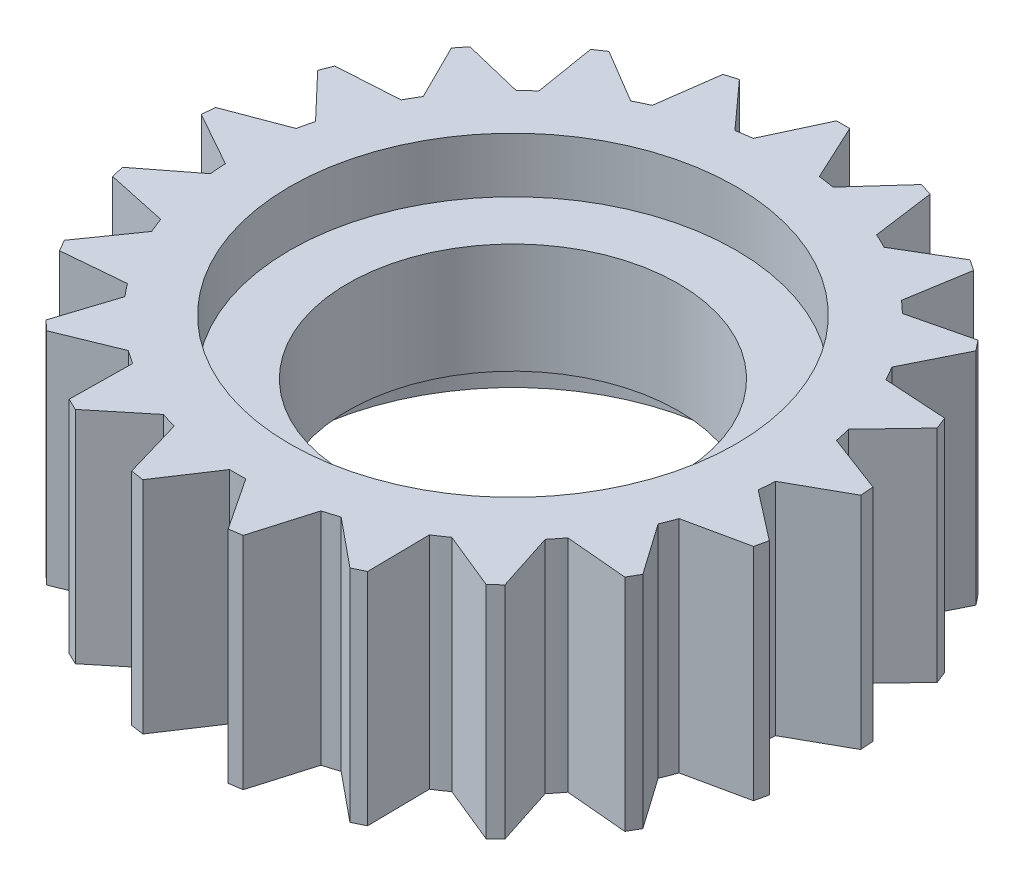
SolidWorks part; units mm, degrees
ref_plane "Front Plane" through (0, 0, 0) normal (0, 0, 1) x (1, 0, 0)
ref_plane "Top Plane" through (0, 0, 0) normal (0, 1, 0) x (1, 0, 0)
ref_plane "Right Plane" through (0, 0, 0) normal (1, 0, 0) x (0, 0, -1)
sketch "Sketch1" plane through (0, 0, 0) normal (1, 0, 0) x (0, 0, -1)
  line L0 (0, 0) -> (0, 16285.2798) construction
  line L1 (0, 0) -> (16285.2798, 0) construction
  line L2 (20.25, 10) -> (30, 10)
  line L3 (30, 10) -> (30, -10)
  line L4 (30, -10) -> (20.25, -10)
  line L5 (20.25, -10) -> (20.25, -5)
  line L6 (20.25, -5) -> (15, -5)
  line L7 (15, -5) -> (15, 5)
  line L8 (15, 5) -> (20.25, 5)
  line L9 (20.25, 5) -> (20.25, 10)
  dimension "D1" = 60
  dimension "D2" = 40.5
  dimension "D3" = 30
  dimension "D4" = 10
  dimension "D5" = 20
revolve "Revolve1" add sketch "Sketch1" angle 360 about L0
sketch "Sketch2" plane through (0, 10, 0) normal (0, 1, 0) x (1, 0, 0)
  line L0 (0, 0) -> (50000, 0) construction
  line L1 (0, 0) -> (0, 50000) construction
  line L2 (-0.6, 29.9781) -> (0.6, 29.9781)
  line L3 (0.6, 29.9781) -> (3, 24.8193)
  line L4 (-0.6, 29.9781) -> (-3, 24.8193)
  line L5 (8.2629, 28.8231) -> (4.4489, 24.601)
  line L6 (8.2629, 28.8231) -> (9.4095, 28.4694)
  line L7 (9.4095, 28.4694) -> (10.1823, 22.8324)
  line L8 (16.3915, 25.107) -> (11.5025, 22.1967)
  line L9 (16.3915, 25.107) -> (17.383, 24.4311)
  line L10 (17.383, 24.4311) -> (16.46, 18.8167)
  line L11 (23.0637, 19.1601) -> (17.5341, 17.8201)
  line L12 (23.0637, 19.1601) -> (23.8119, 18.2219)
  line L13 (23.8119, 18.2219) -> (21.275, 13.1291)
  line L14 (27.6866, 11.5107) -> (22.0077, 11.8601)
  line L15 (27.6866, 11.5107) -> (28.125, 10.3937)
  line L16 (28.125, 10.3937) -> (24.1997, 6.2749)
  line L17 (29.8494, 2.8386) -> (24.5258, 4.8464)
  line L18 (29.8494, 2.8386) -> (29.9391, 1.6419)
  line L19 (29.9391, 1.6419) -> (24.9741, -1.1369)
  line L20 (29.36, -6.0858) -> (24.8646, -2.598)
  line L21 (29.36, -6.0858) -> (29.093, -7.2557)
  line L22 (29.093, -7.2557) -> (23.5295, -8.4476)
  line L23 (26.2618, -14.4694) -> (22.9942, -9.8116)
  line L24 (26.2618, -14.4694) -> (25.6618, -15.5087)
  line L25 (25.6618, -15.5087) -> (19.9942, -15.0077)
  line L26 (20.8301, -21.5674) -> (19.0806, -16.1534)
  line L27 (20.8301, -21.5674) -> (19.9504, -22.3836)
  line L28 (19.9504, -22.3836) -> (14.6823, -20.2344)
  line L29 (13.5476, -26.749) -> (13.4716, -21.0598)
  line L30 (13.5476, -26.749) -> (12.4664, -27.2696)
  line L31 (12.4664, -27.2696) -> (8.0658, -23.6631)
  line L32 (5.0613, -29.5538) -> (6.6656, -24.095)
  line L33 (5.0613, -29.5538) -> (3.8747, -29.7327)
  line L34 (3.8747, -29.7327) -> (0.7326, -24.9893)
  line L35 (-3.8747, -29.7327) -> (-0.7326, -24.9893)
  line L36 (-3.8747, -29.7327) -> (-5.0613, -29.5538)
  line L37 (-5.0613, -29.5538) -> (-6.6656, -24.095)
  line L38 (-12.4664, -27.2696) -> (-8.0658, -23.6631)
  line L39 (-12.4664, -27.2696) -> (-13.5476, -26.749)
  line L40 (-13.5476, -26.749) -> (-13.4716, -21.0598)
  line L41 (-19.9504, -22.3836) -> (-14.6823, -20.2344)
  line L42 (-19.9504, -22.3836) -> (-20.8301, -21.5674)
  line L43 (-20.8301, -21.5674) -> (-19.0806, -16.1534)
  line L44 (-25.6618, -15.5087) -> (-19.9942, -15.0077)
  line L45 (-25.6618, -15.5087) -> (-26.2618, -14.4694)
  line L46 (-26.2618, -14.4694) -> (-22.9942, -9.8116)
  line L47 (-29.093, -7.2557) -> (-23.5295, -8.4476)
  line L48 (-29.093, -7.2557) -> (-29.36, -6.0858)
  line L49 (-29.36, -6.0858) -> (-24.8646, -2.598)
  line L50 (-29.9391, 1.6419) -> (-24.9741, -1.1369)
  line L51 (-29.9391, 1.6419) -> (-29.8494, 2.8386)
  line L52 (-29.8494, 2.8386) -> (-24.5258, 4.8464)
  line L53 (-28.125, 10.3937) -> (-24.1997, 6.2749)
  line L54 (-28.125, 10.3937) -> (-27.6866, 11.5107)
  line L55 (-27.6866, 11.5107) -> (-22.0077, 11.8601)
  line L56 (-23.8119, 18.2219) -> (-21.275, 13.1291)
  line L57 (-23.8119, 18.2219) -> (-23.0637, 19.1601)
  line L58 (-23.0637, 19.1601) -> (-17.5341, 17.8201)
  line L59 (-17.383, 24.4311) -> (-16.46, 18.8167)
  line L60 (-17.383, 24.4311) -> (-16.3915, 25.107)
  line L61 (-16.3915, 25.107) -> (-11.5025, 22.1967)
  line L62 (-9.4095, 28.4694) -> (-10.1823, 22.8324)
  line L63 (-9.4095, 28.4694) -> (-8.2629, 28.8231)
  line L64 (-8.2629, 28.8231) -> (-4.4489, 24.601)
  circle A0 centre (0, 0) radius 25
  circle A1 centre (0, 0) radius 30 construction
  circle A2 centre (0, 0) radius 30
  point P10 (0, 29.9781)
  point P13 (0, 0)
  point P17 (8.8362, 28.6462)
  point P22 (16.8873, 24.7691)
  point P27 (23.4378, 18.691)
  point P32 (27.9058, 10.9522)
  point P37 (29.8943, 2.2403)
  point P42 (29.2265, -6.6708)
  point P47 (25.9618, -14.989)
  point P52 (20.3903, -21.9755)
  point P57 (13.007, -27.0093)
  point P62 (4.468, -29.6433)
  point P67 (-4.468, -29.6433)
  point P72 (-13.007, -27.0093)
  point P77 (-20.3903, -21.9755)
  point P82 (-25.9618, -14.989)
  point P87 (-29.2265, -6.6708)
  point P92 (-29.8943, 2.2403)
  point P97 (-27.9058, 10.9522)
  point P102 (-23.4378, 18.691)
  point P107 (-16.8873, 24.7691)
  point P112 (-8.8362, 28.6462)
  point P114 (0, 0)
  circle M9 centre (0, 0) radius 30
  dimension "D1" = 50
  dimension "D2" = 1.2
  dimension "D3" = 6
  dimension "D4" = 21
extrude "Cut-Extrude1" cut sketch "Sketch2" against normal through all both and the other way through all contours A0 L32 L33 L34 L35 L36 L37 L38 L39 L40 L41 L42 L43 L44 L45 L46 L47 L48 L49 L50 L51 L52 L53 L54 L55 L56 L57 L58 L59 L60 L61 L62 L63 L64 L4 L2 L3 M9
